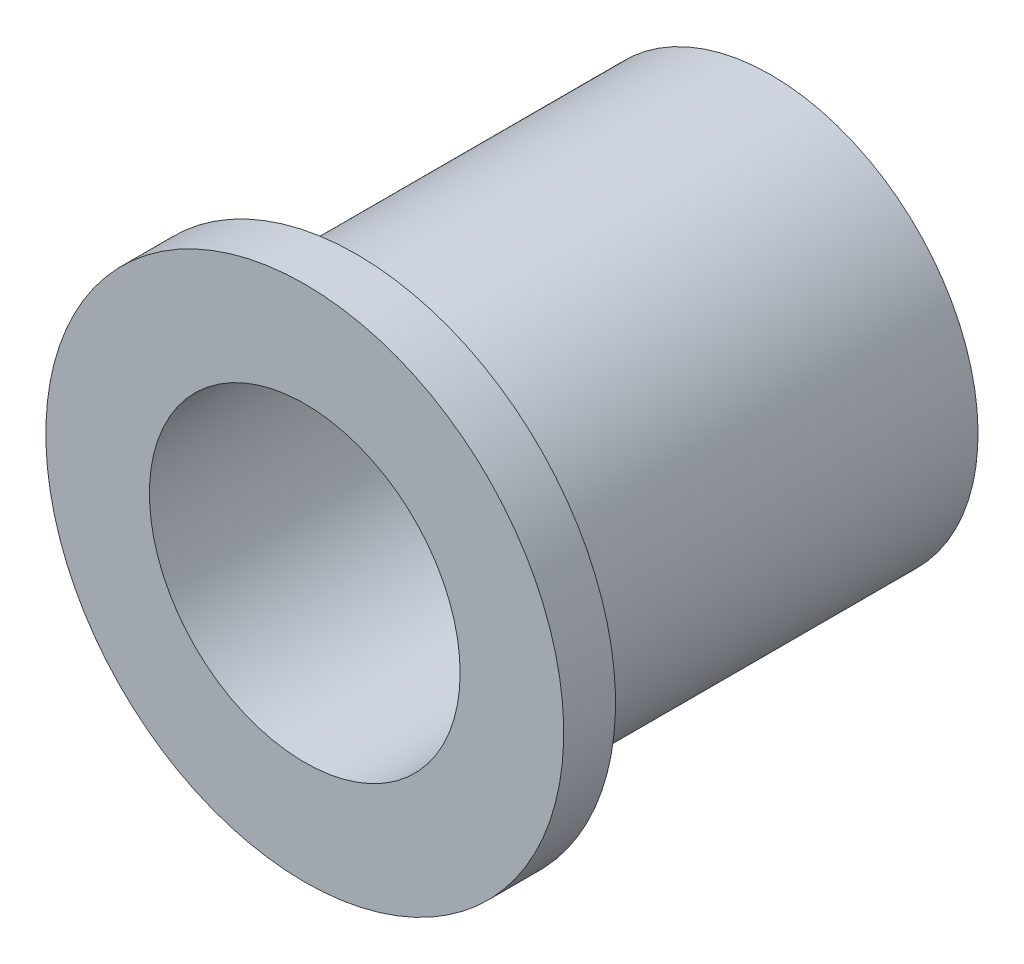
SolidWorks part; units mm, degrees
ref_plane "Front Plane" through (0, 0, 0) normal (0, 0, 1) x (1, 0, 0)
ref_plane "Top Plane" through (0, 0, 0) normal (0, 1, 0) x (1, 0, 0)
ref_plane "Right Plane" through (0, 0, 0) normal (1, 0, 0) x (0, 0, -1)
sketch "Sketch1" plane through (0, 0, 0) normal (1, 0, 0) x (0, 0, -1)
  line L0 (23.1706, 0) -> (-16.8294, 0)
  line L1 (-16.8294, 0) -> (-16.8294, -5)
  line L2 (-16.8294, -5) -> (-21.8294, -5)
  line L3 (-21.8294, -5) -> (-21.8294, 20)
  line L4 (-21.8294, 20) -> (23.1706, 20)
  line L5 (23.1706, 20) -> (23.1706, 0)
  dimension "D1" = 25
  dimension "D2" = 40
  dimension "D3" = 20
  dimension "D4" = 5
revolve "Revolve1" add sketch "Sketch1" angle 360 about L4
sketch "Sketch2" plane through (0, 0, 21.8294) normal (0, 0, 1) x (1, 0, 0)
  circle A0 centre (0, 20) radius 15
  dimension "D1" = 30
extrude "Cut-Extrude1" cut sketch "Sketch2" against normal through all
